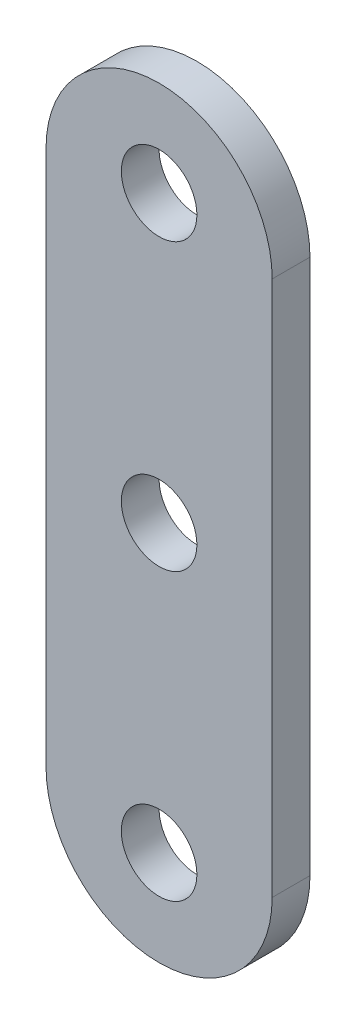
SolidWorks part; units mm, degrees
ref_plane "Front Plane" through (0, 0, 0) normal (0, 0, 1) x (1, 0, 0)
ref_plane "Top Plane" through (0, 0, 0) normal (0, 1, 0) x (1, 0, 0)
ref_plane "Right Plane" through (0, 0, 0) normal (1, 0, 0) x (0, 0, -1)
sketch "Sketch1" plane through (0, 0, 0) normal (0, 0, 1) x (1, 0, 0)
  line L0 (0, -22.5) -> (0, 22.5) construction
  line L1 (-9.5, -22.5) -> (-9.5, 22.5)
  line L2 (9.5, -22.5) -> (9.5, 22.5)
  arc A0 (-9.5, -22.5) -> (9.5, -22.5) centre (0, -22.5) ccw
  arc A1 (9.5, 22.5) -> (-9.5, 22.5) centre (0, 22.5) ccw
  point P2 (0, 0)
  dimension "D1" = 45
  dimension "D2" = 9.5
extrude "Boss-Extrude1" add sketch "Sketch1" along normal blind 3.175
sketch "Sketch2" plane through (0, 0, 3.175) normal (0, 0, 1) x (1, 0, 0)
  circle A0 centre (0, 0) radius 3.175
  dimension "D1" = 6.35
extrude "Cut-Extrude1" cut sketch "Sketch2" against normal through all
pattern_linear "LPattern1" count 2 spacing 24 along (0, 1, 0) count 2 spacing 24 along (0, -1, 0) of "Cut-Extrude1"
